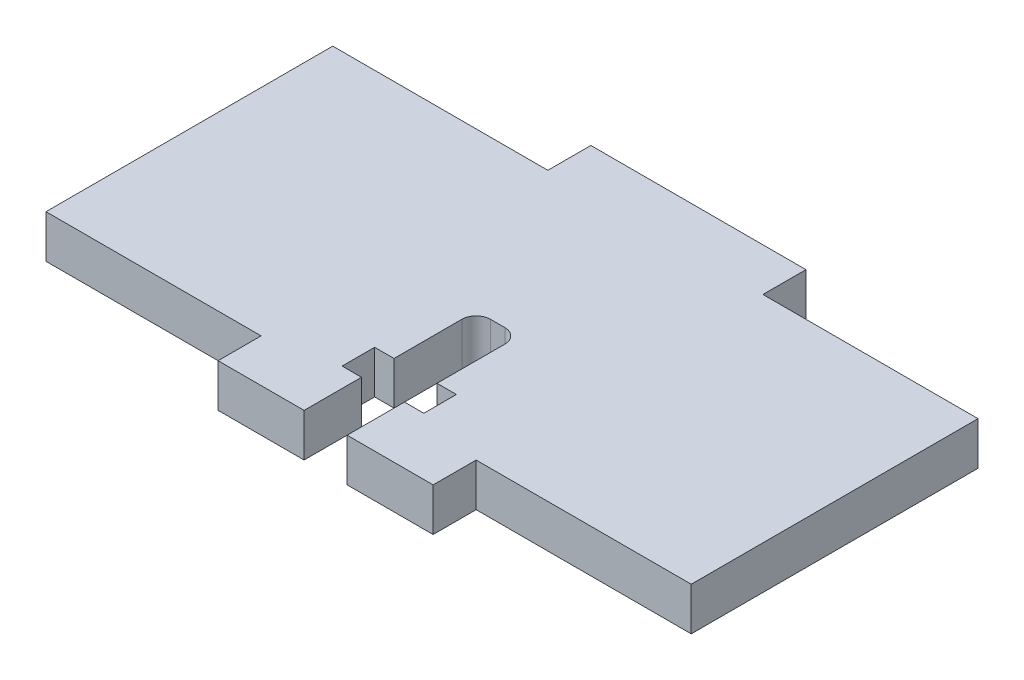
SolidWorks part; units mm, degrees
ref_plane "Plano frontal" through (0, 0, 0) normal (0, 0, 1) x (1, 0, 0)
ref_plane "Plano superior" through (0, 0, 0) normal (0, 1, 0) x (1, 0, 0)
ref_plane "Plano direito" through (0, 0, 0) normal (1, 0, 0) x (0, 0, -1)
sketch "Sketch1" plane through (0, 0, 0) normal (0, 1, 0) x (1, 0, 0)
  line L1 (22.5, -10) -> (-22.5, -10)
  line L2 (22.5, -10) -> (22.5, 10)
  line L3 (22.5, 10) -> (-22.5, 10)
  line L4 (-22.5, -10) -> (-22.5, 10)
  line L5 (22.5, -10) -> (-22.5, 10) construction
  line L6 (22.5, 10) -> (-22.5, -10) construction
  point P0 (0, 0)
  dimension "D1" = 45
  dimension "D2" = 20
extrude "Boss-Extrude1" add sketch "Sketch1" along normal mid plane 3
sketch "Sketch2" plane through (0, 0, 0) normal (0, 1, 0) x (1, 0, 0)
  line L0 (-22.5, -10) -> (22.5, -10) construction
  line L1 (-7.5, -10) -> (7.5, -10)
  line L2 (-7.5, -10) -> (-7.5, -13)
  line L3 (-7.5, -13) -> (7.5, -13)
  line L4 (7.5, -10) -> (7.5, -13)
  line L5 (-1.65, 0) -> (1.65, 0) construction
  line L6 (7.5, 10) -> (7.5, 13)
  line L7 (-7.5, 13) -> (7.5, 13)
  line L8 (-7.5, 10) -> (-7.5, 13)
  line L9 (-7.5, 10) -> (7.5, 10)
  point P6 (0, -10)
  dimension "D1" = 3
  dimension "D2" = 15
extrude "Boss-Extrude2" add sketch "Sketch2" along normal mid plane 3
sketch "Sketch3" plane through (0, 0, 0) normal (0, 1, 0) x (1, 0, 0)
  line L0 (-7.5, -13) -> (7.5, -13) construction
  line L1 (-1.5, -13) -> (1.5, -13)
  line L2 (-1.5, -13) -> (-1.5, -9)
  line L3 (-0.5, -1) -> (0.5, -1)
  line L4 (1.5, -13) -> (1.5, -9)
  line L5 (1.5, -6.73) -> (2.85, -6.73)
  line L6 (-2.85, -6.73) -> (-1.5, -6.73)
  line L7 (-2.85, -6.73) -> (-2.85, -9)
  line L8 (-2.85, -9) -> (-1.5, -9)
  line L9 (2.85, -6.73) -> (2.85, -9)
  line L10 (-1.5, -6.73) -> (-1.5, -2)
  line L11 (1.5, -9) -> (2.85, -9)
  line L12 (1.5, -6.73) -> (1.5, -2)
  arc A0 (0.5, -1) -> (1.5, -2) centre (0.5, -2) cw
  arc A1 (-1.5, -2) -> (-0.5, -1) centre (-0.5, -2) cw
  point P6 (0, -1)
  point P14 (1.5, -1)
  point P17 (-1.5, -1)
  dimension "D7" = 1
  dimension "D1" = 3
  dimension "D2" = 12
  dimension "D3" = 1.35
  dimension "D4" = 1.35
  dimension "D5" = 2.27
  dimension "D6" = 4
extrude "Cut-Extrude1" cut sketch "Sketch3" against normal through all both and the other way through all
